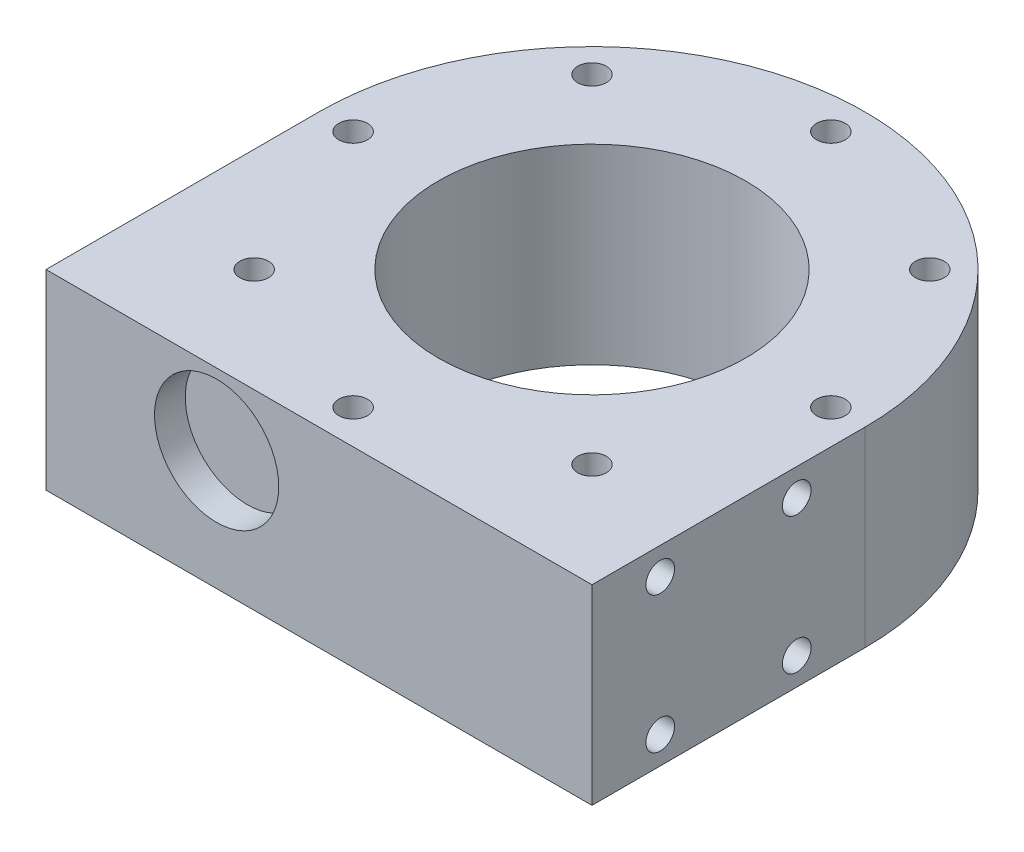
SolidWorks part; units mm, degrees
material "ABS"
ref_plane "前视基准面" through (0, 0, 0) normal (0, 0, 1) x (1, 0, 0)
ref_plane "上视基准面" through (0, 0, 0) normal (0, 1, 0) x (1, 0, 0)
ref_plane "右视基准面" through (0, 0, 0) normal (1, 0, 0) x (0, 0, -1)
other "Configuration Table"
sketch "草图1" plane through (0, 0, 0) normal (0, 1, 0) x (1, 0, 0)
  line L2 (-40, 0) -> (-40, -40)
  line L3 (-40, -40) -> (40, -40)
  line L4 (40, 0) -> (40, -40)
  arc A0 (40, 0) -> (-40, 0) centre (0, 0) ccw
  circle A1 centre (0, 0) radius 22.5
  dimension "D1" = 80
  dimension "D2" = 45
extrude "凸台-拉伸1" add sketch "草图1" along normal blind 28
sketch "草图2" plane through (0, 28, 0) normal (0, 1, 0) x (1, 0, 0)
  circle A0 centre (0, 0) radius 35 construction
  circle A1 centre (0, 35) radius 2.1
  circle A2 centre (24.7487, 24.7487) radius 2.1
  circle A3 centre (35, 0) radius 2.1
  circle A4 centre (24.7487, -24.7487) radius 2.1
  circle A5 centre (0, -35) radius 2.1
  circle A6 centre (-24.7487, -24.7487) radius 2.1
  circle A7 centre (-35, 0) radius 2.1
  circle A8 centre (-24.7487, 24.7487) radius 2.1
  point P21 (0, 0)
  dimension "D1" = 70
  dimension "D2" = 4.2
  dimension "D3" = 8
extrude "切除-拉伸1" cut sketch "草图2" against normal through all
sketch "草图6" plane through (0, 0, 40) normal (0, 0, 1) x (1, 0, 0)
  line L0 (-40, 28) -> (-40, 0) construction
  line L1 (-40, 0) -> (40, 0) construction
  circle A0 centre (-15, 17.5) radius 9.1
  dimension "D1" = 18.2
  dimension "D2" = 25
  dimension "D3" = 17.5
extrude "切除-拉伸2" cut sketch "草图6" against normal blind 4.5
sketch "草图7" plane through (-40, 0, 0) normal (-1, 0, 0) x (0, 0, 1)
  line L0 (20, 28) -> (20, 0) construction
  line L1 (0, 28) -> (40, 28) construction
  line L2 (0, 0) -> (40, 0) construction
  line L4 (10, 24) -> (30, 24) construction
  line L5 (10, 24) -> (10, 4) construction
  line L6 (10, 4) -> (30, 4) construction
  line L7 (30, 24) -> (30, 4) construction
  line L8 (20, 4) -> (20, 24) construction
  line L9 (10, 14) -> (30, 14) construction
  circle A0 centre (10, 24) radius 2.1
  circle A1 centre (30, 24) radius 2.1
  circle A2 centre (10, 4) radius 2.1
  circle A3 centre (30, 4) radius 2.1
  point P6 (20, 14)
  dimension "D3" = 4.2
  dimension "D1" = 20
  dimension "D2" = 20
extrude "切除-拉伸3" cut sketch "草图7" against normal blind 4
ref_plane "基准面1" through (0, 0, 0) normal (-1, 0, 0) x (0, 0, 1)
mirror "镜向1" about plane through (0, 0, 0) normal (-1, 0, 0) of "切除-拉伸3"
